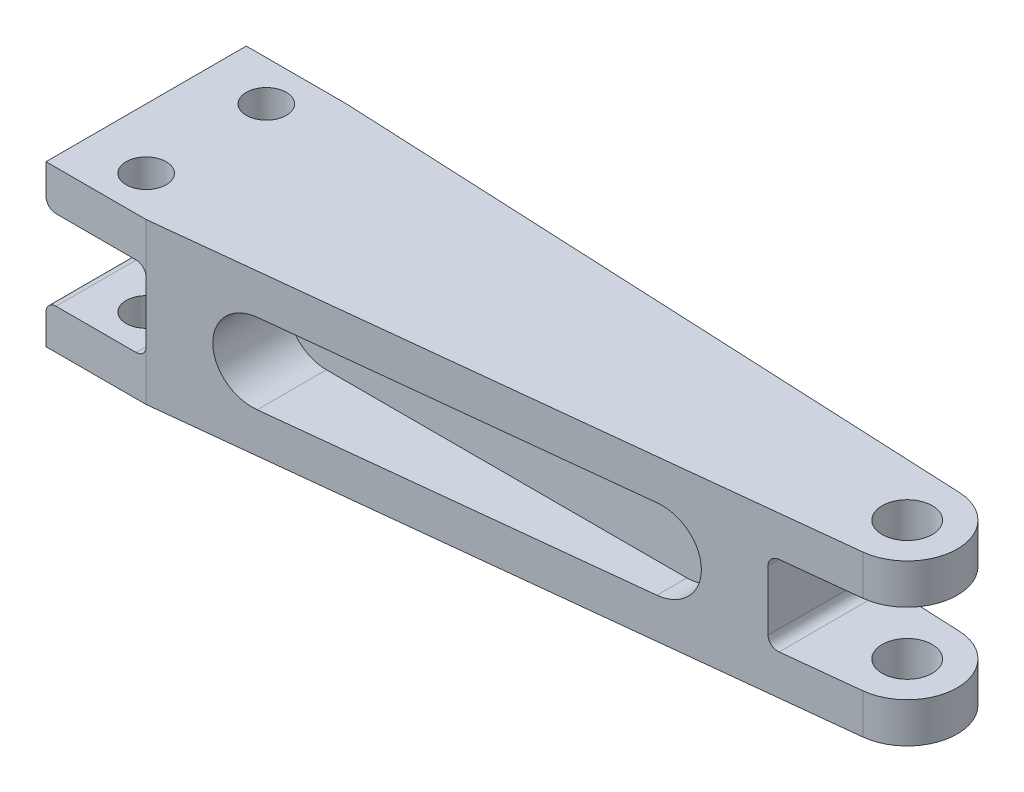
SolidWorks part; units mm, degrees
material "6061-T6 (SS)"
ref_plane "Front Plane" through (0, 0, 0) normal (0, 0, 1) x (1, 0, 0)
ref_plane "Top Plane" through (0, 0, 0) normal (0, 1, 0) x (1, 0, 0)
ref_plane "Right Plane" through (0, 0, 0) normal (1, 0, 0) x (0, 0, -1)
sketch "Sketch1" plane through (0, 0, 0) normal (0, 1, 0) x (1, 0, 0)
  line L0 (0, 0) -> (-54.4242, 0) construction
  line L1 (-117.475, 12.7) -> (-101.6, 12.7)
  line L2 (-117.475, 12.7) -> (-117.475, -19.05)
  line L3 (-117.475, -19.05) -> (-101.6, -19.05)
  line L4 (-101.6, -19.05) -> (0.8594, -7.8908)
  line L5 (-107.95, 6.35) -> (-107.95, -12.7) construction
  line L6 (-120.65, 18.1036) -> (-120.65, -23.5643) construction
  line L7 (-158.75, 18.1036) -> (-158.75, -23.5643) construction
  line L8 (-117.475, -3.175) -> (-107.95, -3.175) construction
  line L9 (-101.6, 12.7) -> (0.371, 7.9288)
  circle A0 centre (0, 0) radius 3.9688
  arc A1 (0.371, 7.9288) -> (0.8594, -7.8908) centre (0, 0) cw
  circle A2 centre (-107.95, 6.35) radius 3.175
  circle A3 centre (-107.95, -12.7) radius 3.175
  point P17 (-158.75, -6.35)
  dimension "D1" = 7.9375
  dimension "D5" = 6.35
  dimension "D3" = 7.9375
  dimension "D2" = 31.75
  dimension "D4" = 15.875
  dimension "D6" = 38.1
  dimension "D7" = 12.7
  dimension "D8" = 158.75
  dimension "D9" = 19.05
  dimension "D10" = 6.35
  dimension "D11" = 3.175
  dimension "D12" = 19.05
extrude "Boss-Extrude1" add sketch "Sketch1" along normal mid plane 25.4
sketch "Sketch2" plane through (0, 0, 0) normal (0, 0, 1) x (1, 0, 0)
  line L1 (-12.7, 6.35) -> (12.7, 6.35)
  line L2 (-12.7, 6.35) -> (-12.7, -6.35)
  line L3 (-12.7, -6.35) -> (12.7, -6.35)
  line L4 (12.7, 6.35) -> (12.7, -6.35)
  line L5 (-12.7, 6.35) -> (12.7, -6.35) construction
  line L6 (-12.7, -6.35) -> (12.7, 6.35) construction
  line L7 (-117.475, 0) -> (-101.6, 0) construction
  line L8 (-101.6, 6.35) -> (-120.65, 6.35)
  line L9 (-101.6, 6.35) -> (-101.6, -6.35)
  line L10 (-101.6, -6.35) -> (-120.65, -6.35)
  line L11 (-120.65, 6.35) -> (-120.65, -6.35)
  line L12 (-101.6, 6.35) -> (-120.65, -6.35) construction
  line L13 (-101.6, -6.35) -> (-120.65, 6.35) construction
  point P0 (0, 0)
  point P8 (-111.125, 0)
  point P15 (-120.65, 0)
  dimension "D1" = 12.7
  dimension "D2" = 19.05
  dimension "D3" = 12.7
  dimension "D4" = 12.7
extrude "Cut-Extrude1" cut sketch "Sketch2" against normal through all and the other way through all
fillet "Fillet1" radius 1.5875 4 edges at (-12.7, 6.35, 0.4136) (-12.7, -6.35, 0.4136) (-101.6, -6.35, 3.175) (-101.6, 6.35, 3.175)
fillet "Fillet2" radius 1.5875 2 edges at (-117.475, 6.35, 3.175) (-117.475, -6.35, 3.175)
sketch "Sketch3" plane through (0, 0, -12.7) normal (0, 0, -1) x (-1, 0, 0)
  line L0 (28.575, 0) -> (85.725, 0) construction
  line L1 (101.6, 0) -> (-0.8594, 0) construction
  line L2 (28.575, 6.35) -> (85.725, 6.35)
  line L3 (28.575, -6.35) -> (85.725, -6.35)
  line L4 (22.225, 0) -> (12.7, 0) construction
  line L6 (92.075, 0) -> (101.6, 0) construction
  line L8 (101.6, -4.7625) -> (101.6, 4.7625) construction
  line L9 (12.7, 4.7625) -> (12.7, -4.7625) construction
  arc A0 (28.575, 6.35) -> (28.575, -6.35) centre (28.575, 0) ccw
  arc A1 (85.725, -6.35) -> (85.725, 6.35) centre (85.725, 0) ccw
  point P4 (57.15, 0)
  dimension "D1" = 12.7
  dimension "D2" = 9.525
  dimension "D3" = 57.15
extrude "Cut-Extrude2" cut sketch "Sketch3" against normal blind 12.7
sketch "Sketch4" plane through (0, 0, 19.05) normal (0, 0, 1) x (1, 0, 0)
  line L0 (-28.575, 6.35) -> (-85.725, 6.35) construction
  line L1 (-28.575, -6.35) -> (-85.725, -6.35) construction
  line L2 (-28.575, 6.35) -> (-85.725, 6.35)
  line L3 (-28.575, -6.35) -> (-85.725, -6.35)
  arc A0 (-85.725, 6.35) -> (-85.725, -6.35) centre (-85.725, 0) ccw construction
  arc A1 (-28.575, -6.35) -> (-28.575, 6.35) centre (-28.575, 0) ccw construction
  arc A2 (-85.725, 6.35) -> (-85.725, -6.35) centre (-85.725, 0) ccw
  arc A3 (-28.575, -6.35) -> (-28.575, 6.35) centre (-28.575, 0) ccw
extrude "Cut-Extrude3" cut sketch "Sketch4" against normal blind 12.7
